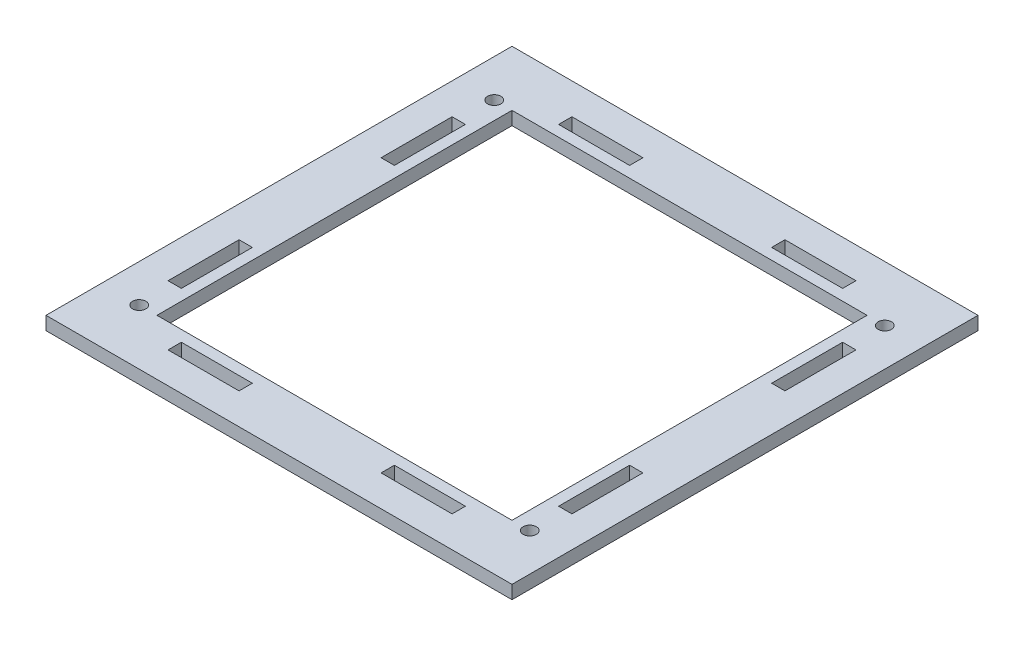
SolidWorks part; units mm, degrees
ref_plane "Front" through (0, 0, 0) normal (0, 0, 1) x (1, 0, 0)
ref_plane "Top" through (0, 0, 0) normal (0, 1, 0) x (1, 0, 0)
ref_plane "Right" through (0, 0, 0) normal (1, 0, 0) x (0, 0, -1)
sketch "Croquis1" plane through (0, 0, 0) normal (0, 1, 0) x (1, 0, 0)
  line L1 (0, 0) -> (80, 0)
  line L2 (0, 0) -> (0, 80)
  line L3 (0, 80) -> (80, 80)
  line L4 (80, 0) -> (80, 80)
  line L5 (0, 0) -> (80, 80) construction
  line L6 (0, 80) -> (80, 0) construction
  line L10 (-12.5, 40) -> (92.5, 40) construction
  line L11 (-12.5, 92.5) -> (92.5, 92.5)
  line L12 (-12.5, 92.5) -> (-12.5, -12.5)
  line L13 (-12.5, -12.5) -> (92.5, -12.5)
  line L14 (92.5, 92.5) -> (92.5, -12.5)
  line L15 (-12.5, 92.5) -> (92.5, -12.5) construction
  line L16 (-12.5, -12.5) -> (92.5, 92.5) construction
  line L21 (40, -12.5) -> (40, -5.5) construction
  line L22 (40, -5.5) -> (24, -5.5) construction
  line L23 (56, -2.5) -> (72, -5.5) construction
  line L24 (24, -5.5) -> (8, -5.5)
  line L29 (84, 40) -> (84, 64) construction
  line L30 (82.5, 24) -> (85.5, 8) construction
  line L31 (82.5, 72) -> (85.5, 72)
  line L32 (82.5, 72) -> (82.5, 56)
  line L33 (82.5, 56) -> (85.5, 56)
  line L34 (85.5, 72) -> (85.5, 56)
  line L35 (82.5, 72) -> (85.5, 56) construction
  line L36 (82.5, 56) -> (85.5, 72) construction
  line L37 (82.5, 8) -> (85.5, 24) construction
  line L38 (85.5, 8) -> (85.5, 24)
  line L39 (82.5, 24) -> (85.5, 24)
  line L40 (82.5, 8) -> (82.5, 24)
  line L41 (82.5, 8) -> (85.5, 8)
  line L42 (40, 93.5) -> (40, 0) construction
  line L43 (-2.5, 8) -> (-5.5, 24) construction
  line L44 (-2.5, 24) -> (-5.5, 8) construction
  line L45 (-2.5, 8) -> (-5.5, 8)
  line L46 (-2.5, 8) -> (-2.5, 24)
  line L47 (-2.5, 24) -> (-5.5, 24)
  line L48 (-5.5, 8) -> (-5.5, 24)
  line L49 (-2.5, 56) -> (-5.5, 72) construction
  line L50 (-2.5, 72) -> (-5.5, 56) construction
  line L51 (-5.5, 72) -> (-5.5, 56)
  line L52 (-2.5, 56) -> (-5.5, 56)
  line L53 (-2.5, 72) -> (-2.5, 56)
  line L54 (-2.5, 72) -> (-5.5, 72)
  line L55 (84, 16) -> (84, 0) construction
  line L56 (24, -5.5) -> (24, -2.5)
  line L57 (24, -2.5) -> (8, -2.5)
  line L58 (8, -5.5) -> (8, -2.5)
  line L59 (24, -5.5) -> (8, -2.5) construction
  line L60 (24, -2.5) -> (8, -5.5) construction
  line L61 (56, -5.5) -> (72, -2.5) construction
  line L62 (72, -5.5) -> (72, -2.5)
  line L63 (56, -2.5) -> (72, -2.5)
  line L64 (56, -5.5) -> (56, -2.5)
  line L65 (56, -5.5) -> (72, -5.5)
  line L66 (56, 85.5) -> (72, 82.5) construction
  line L67 (24, 82.5) -> (8, 85.5) construction
  line L68 (24, 85.5) -> (8, 82.5) construction
  line L69 (56, 82.5) -> (72, 85.5) construction
  line L70 (40, 85.5) -> (24, 85.5) construction
  line L71 (40, 92.5) -> (40, 85.5) construction
  line L72 (56, 85.5) -> (72, 85.5)
  line L73 (56, 85.5) -> (56, 82.5)
  line L74 (56, 82.5) -> (72, 82.5)
  line L75 (72, 85.5) -> (72, 82.5)
  line L76 (8, 85.5) -> (8, 82.5)
  line L77 (24, 82.5) -> (8, 82.5)
  line L78 (24, 85.5) -> (24, 82.5)
  line L79 (24, 85.5) -> (8, 85.5)
  circle A0 centre (84, 0) radius 1.5
  circle A1 centre (84, 80) radius 1.5
  circle A2 centre (-4, 80) radius 1.5
  circle A3 centre (-4, 0) radius 1.5
  point P4 (40, 40)
  point P10 (40, 40)
  point P21 (16, -4)
  point P57 (64, -4)
  point P68 (64, 84)
  point P69 (16, 84)
  dimension "D11" = 3
  dimension "D2" = 105
  dimension "D3" = 105
  dimension "D4" = 10
  dimension "D5" = 16
  dimension "D6" = 16
  dimension "D7" = 3
  dimension "D8" = 4
  dimension "D9" = 16
  dimension "D10" = 16
  dimension "D12" = 16
  dimension "D13" = 3
  dimension "D14" = 80
extrude "Saliente-Extruir1" add sketch "Croquis1" along normal blind 3
